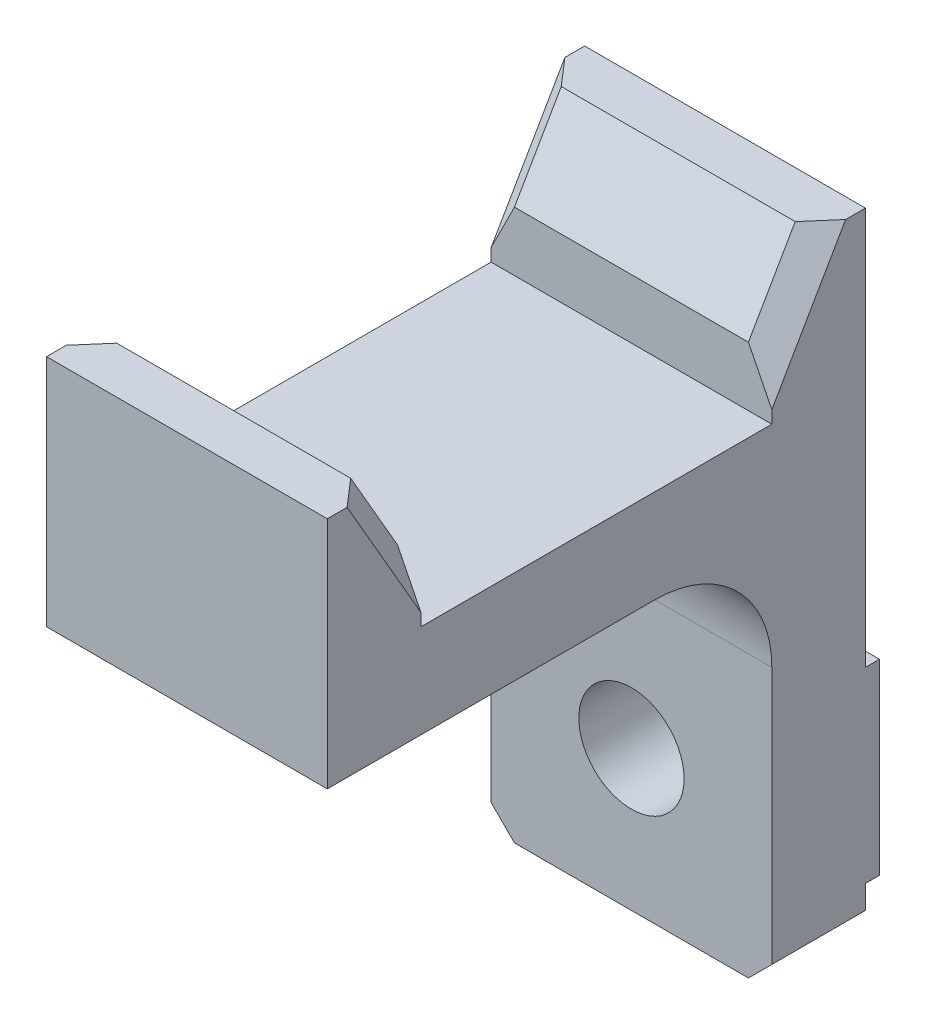
SolidWorks part; units mm, degrees
material "3D printed plastic"
ref_plane "Front Plane" through (0, 0, 0) normal (0, 0, 1) x (1, 0, 0)
ref_plane "Top Plane" through (0, 0, 0) normal (0, 1, 0) x (1, 0, 0)
ref_plane "Right Plane" through (0, 0, 0) normal (1, 0, 0) x (0, 0, -1)
sketch "Sketch1" plane through (0, 0, 0) normal (1, 0, 0) x (0, 0, -1)
  line L0 (7.5, 6) -> (11.5, 6)
  line L1 (-7.5, 0) -> (7.5, 0)
  line L2 (-7.5, 0) -> (-7.5, 6)
  line L3 (11.5, -19) -> (11.5, -21)
  line L4 (7.5, 0) -> (7.5, 6)
  line L5 (-11.5, 6) -> (-7.5, 6)
  line L6 (-11.5, 6) -> (-11.5, -4)
  line L7 (-11.5, -4) -> (7.5, -4)
  line L8 (11.5, 6) -> (11.5, -11)
  line L9 (11.5, -11) -> (12.1, -11)
  line L10 (12.1, -15) -> (8.9316, -15) construction
  line L11 (11.5, -21) -> (7.5, -21)
  line L12 (7.5, -4) -> (7.5, -21)
  line L13 (11.5, -19) -> (12.1, -19)
  line L14 (12.1, -11) -> (12.1, -19)
  dimension "D1" = 15
  dimension "D2" = 4
  dimension "D3" = 4
  dimension "D4" = 6
  dimension "D5" = 4
  dimension "D6" = 21
  dimension "D7" = 8
  dimension "D8" = 0.6
  dimension "D9" = 15
extrude "Boss-Extrude1" add sketch "Sketch1" along normal mid plane 12
sketch "Sketch2" plane through (0, 0, -7.5) normal (0, 0, 1) x (1, 0, 0)
  line L0 (0, 0) -> (0, -15) construction
  line L1 (0, -15) -> (6, -15) construction
  line L2 (6, -4) -> (6, -21) construction
  line L3 (6, -19) -> (6, -11) construction
  circle A0 centre (0, -15) radius 2.25
  dimension "D2" = 4.5
extrude "Cut-Extrude1" cut sketch "Sketch2" against normal through all
chamfer "Chamfer1" distance 2 angle 60 2 edges at (0, 6, 7.5) (0, 6, -7.5)
chamfer "Chamfer3" distance 1 angle 45 4 edges at (-6, 4.2679, 8.5) (6, 4.2679, 8.5) (-6, 4.2679, -8.5) (6, 4.2679, -8.5)
chamfer "Chamfer4" distance 1 angle 45 2 edges at (-6, -21, -9.5) (6, -21, -9.5)
fillet "Fillet1" radius 5 1 edges at (0, -4, -7.5)
